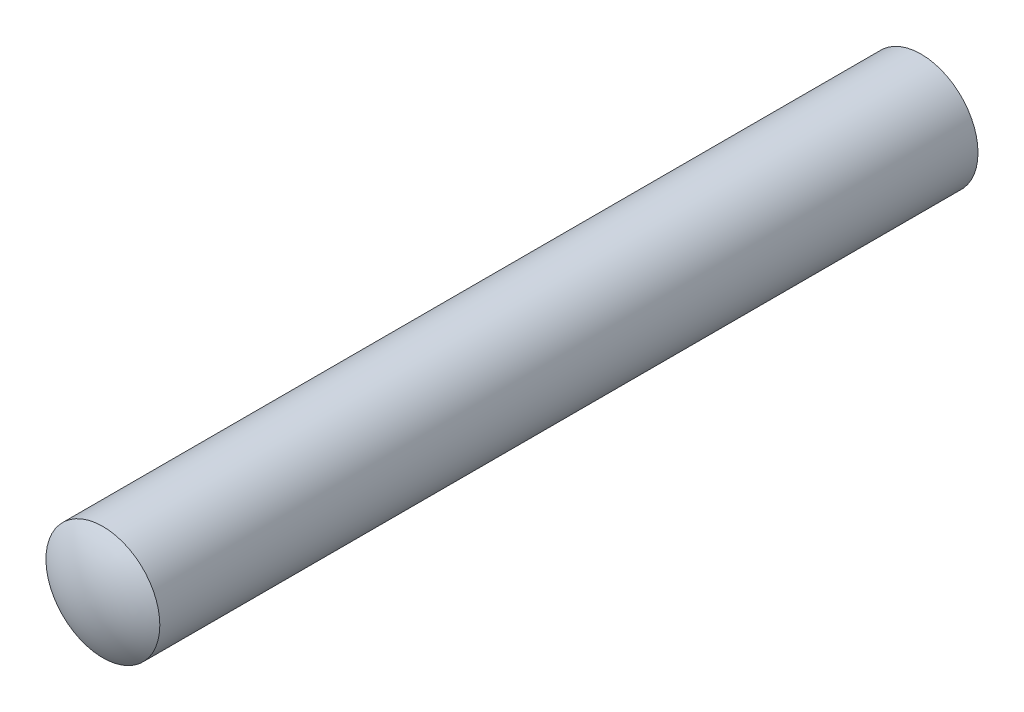
SolidWorks part; units mm, degrees
ref_plane "前基準面" through (0, 0, 0) normal (0, 0, 1) x (1, 0, 0)
ref_plane "上基準面" through (0, 0, 0) normal (0, 1, 0) x (1, 0, 0)
ref_plane "右基準面" through (0, 0, 0) normal (1, 0, 0) x (0, 0, -1)
sketch "草圖1" plane through (0, 0, 0) normal (1, 0, 0) x (0, 0, -1)
  line L0 (-14.37, 2) -> (14.37, 2)
  line L1 (-15, 0) -> (15, 0) construction
  line L2 (15, 0) -> (-15, 0)
  line L3 (0, 0) -> (0, 11.3796) construction
  arc A0 (14.37, 2) -> (15, 0) centre (11.5104, 0) cw
  arc A1 (-14.37, 2) -> (-15, 0) centre (-11.5104, 0) ccw
  dimension "D1" = 30
  dimension "D2" = 4
  dimension "D3" = 0.63
  dimension "D4" = 0.63
revolve "旋轉1" add sketch "草圖1" angle 360 about L1
